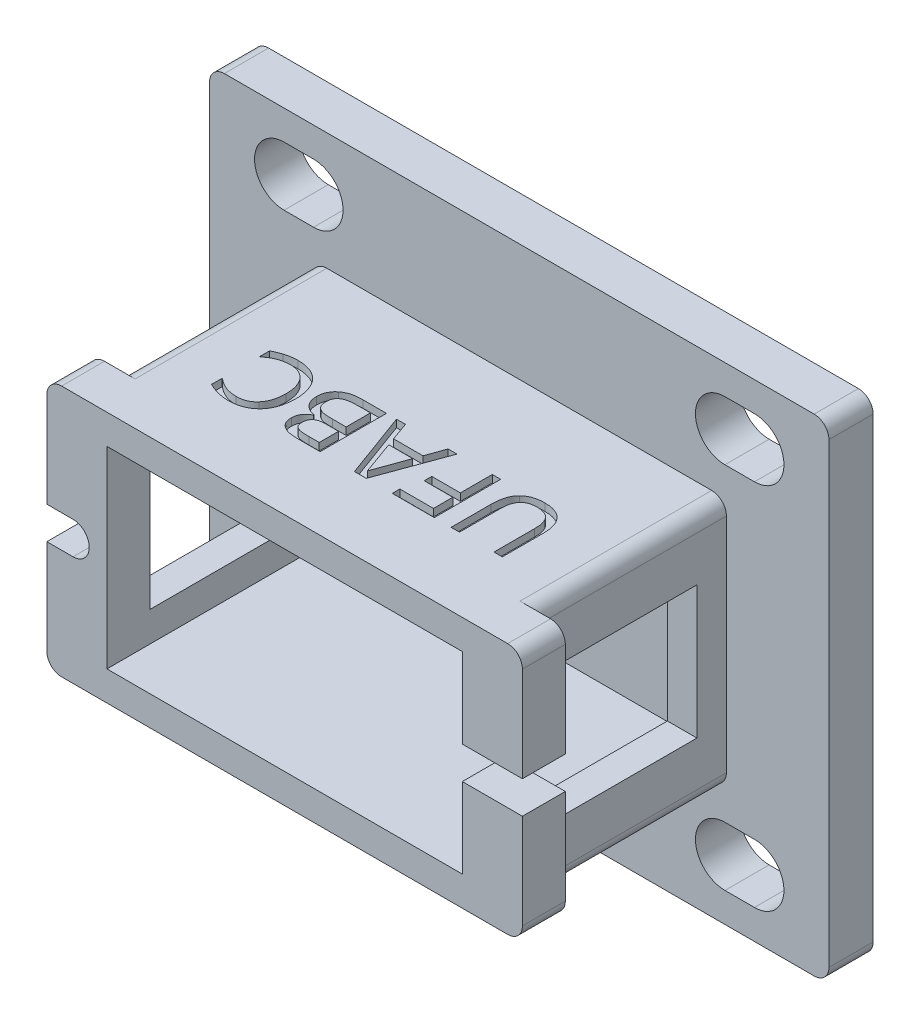
SolidWorks part; units mm, degrees
material "ABS"
ref_plane "Plano frontal" through (0, 0, 0) normal (0, 0, 1) x (1, 0, 0)
ref_plane "Plano superior" through (0, 0, 0) normal (0, 1, 0) x (1, 0, 0)
ref_plane "Plano direito" through (0, 0, 0) normal (1, 0, 0) x (0, 0, -1)
sketch "Esboço1" plane through (0, 0, 0) normal (0, 0, 1) x (1, 0, 0)
  line L0 (5.5315, 35.935) -> (5.5315, 2.935) construction
  line L19 (-14.4685, 35.935) -> (25.5315, 35.935)
  line L20 (-15.4685, 34.935) -> (-15.4685, 3.935)
  line L21 (-14.4685, 2.935) -> (25.5315, 2.935)
  line L22 (26.5315, 34.935) -> (26.5315, 3.935)
  arc A0 (26.5315, 34.935) -> (25.5315, 35.935) centre (25.5315, 34.935) ccw
  arc A1 (26.5315, 3.935) -> (25.5315, 2.935) centre (25.5315, 3.935) cw
  arc A2 (-14.4685, 2.935) -> (-15.4685, 3.935) centre (-14.4685, 3.935) cw
  arc A3 (-15.4685, 34.935) -> (-14.4685, 35.935) centre (-14.4685, 34.935) cw
  point P14 (-15.4685, 35.935)
  dimension "D3" = 1
  dimension "D1" = 33
  dimension "D2" = 42
extrude "Ressalto-extrusão1" add sketch "Esboço1" along normal blind 3
sketch "Esboço2" plane through (0, 0, 3) normal (0, 0, 1) x (1, 0, 0)
  line L0 (5.5315, 35.935) -> (5.5315, 2.935) construction
  line L1 (25.5315, 35.935) -> (-14.4685, 35.935) construction
  line L2 (-14.4685, 2.935) -> (25.5315, 2.935) construction
  line L3 (-15.4685, 19.435) -> (26.5315, 19.435) construction
  line L4 (-6.5185, 25.97) -> (17.5815, 25.97)
  line L5 (-6.5185, 25.97) -> (-6.5185, 12.9)
  line L6 (-6.5185, 12.9) -> (17.5815, 12.9)
  line L7 (17.5815, 25.97) -> (17.5815, 12.9)
  line L8 (-8.5185, 27.975) -> (19.5815, 27.975)
  line L9 (-8.5185, 27.975) -> (-8.5185, 10.895)
  line L10 (-8.5185, 10.895) -> (19.5815, 10.895)
  line L11 (19.5815, 27.975) -> (19.5815, 10.895)
  line L12 (-15.4685, 34.935) -> (-15.4685, 3.935) construction
  line L13 (26.5315, 3.935) -> (26.5315, 34.935) construction
  dimension "D1" = 14.05
  dimension "D2" = 14.05
  dimension "D3" = 12.05
  dimension "D4" = 12.05
  dimension "D5" = 8.54
  dimension "D6" = 8.54
  dimension "D7" = 6.535
  dimension "D8" = 6.535
extrude "Ressalto-extrusão2" add sketch "Esboço2" along normal blind 15.91
sketch "Esboço3" plane through (0, 0, 18.91) normal (0, 0, 1) x (1, 0, 0)
  line L0 (5.5315, 25.97) -> (5.5315, 10.895) construction
  line L1 (17.5815, 25.97) -> (-6.5185, 25.97) construction
  line L2 (-8.5185, 10.895) -> (19.5815, 10.895) construction
  line L3 (-15.4685, 19.435) -> (26.5315, 19.435) construction
  line L4 (-15.4685, 34.935) -> (-15.4685, 3.935) construction
  line L5 (26.5315, 3.935) -> (26.5315, 34.935) construction
  line L6 (19.5815, 27.975) -> (-8.5185, 27.975) construction
  line L7 (-8.5185, 27.975) -> (-9.5935, 27.975)
  line L8 (-8.5185, 27.975) -> (-8.5185, 10.895)
  line L9 (-8.5185, 10.895) -> (-9.5935, 10.895)
  line L10 (-10.5935, 26.975) -> (-10.5935, 11.895)
  line L11 (19.5815, 27.975) -> (20.6565, 27.975)
  line L12 (19.5815, 27.975) -> (19.5815, 10.895)
  line L13 (19.5815, 10.895) -> (20.6565, 10.895)
  line L14 (21.6565, 26.975) -> (21.6565, 11.895)
  line L16 (19.5815, 27.975) -> (-8.5185, 27.975) construction
  arc A0 (20.6565, 27.975) -> (21.6565, 26.975) centre (20.6565, 26.975) cw
  arc A1 (20.6565, 10.895) -> (21.6565, 11.895) centre (20.6565, 11.895) ccw
  arc A2 (-9.5935, 10.895) -> (-10.5935, 11.895) centre (-9.5935, 11.895) cw
  arc A3 (-9.5935, 27.975) -> (-10.5935, 26.975) centre (-9.5935, 26.975) ccw
  dimension "D3" = 1
  dimension "D1" = 16.125
  dimension "D2" = 16.125
extrude "Ressalto-extrusão3" add sketch "Esboço3" along direction (0, 0, 1) on the side against the normal offset from surface (2.91 mm away) 13
hole_wizard "Furo com folga de #00002" positions "Esboço8" profile "Esboço7" hole size "#0000" standard "Ansi Inch"
sketch "Esboço8" plane through (0, 0, 18.91) normal (0, 0, 1) x (1, 0, 0)
  line L0 (-10.5935, 19.435) -> (21.6565, 19.435) construction
  line L1 (-10.5935, 26.975) -> (-10.5935, 11.895) construction
  line L2 (21.6565, 11.895) -> (21.6565, 26.975) construction
  line L3 (-6.5185, 25.97) -> (-6.5185, 12.9) construction
  line L4 (17.5815, 12.9) -> (17.5815, 25.97) construction
  point P0 (-8.8185, 19.435)
  point P2 (19.8815, 19.435)
  dimension "D1" = 2.3
  dimension "D2" = 2.3
sketch "Esboço7" plane through (-8.8185, 19.435, 18.91) normal (1, 0, 0) x (0, -1, 0)
  line L0 (0, 0) -> (0, 4.6609)
  line L1 (0, 4.6609) -> (1.1, 4)
  line L2 (1.1, 4) -> (1.1, 0)
  line L5 (1.1, 0) -> (0, 0)
  line L10 (0, 4.6609) -> (-1.1, 4) construction
  line L11 (0, -6.35) -> (0, 107.95) construction
  dimension "Hole Dia." = 2.2
  dimension "Hole Depth" = 4
  dimension "Drill Angle" = 118
ref_plane "Plano1" through (0, 19.435, 0) normal (0, -1, 0) x (-1, 0, 0)
ref_plane "Plano2" through (5.5315, 0, 0) normal (-1, 0, 0) x (0, 0, 1)
sketch "Esboço19" plane through (0, 0, 3) normal (0, 0, 1) x (1, 0, 0)
  line L1 (-8.5185, 10.895) -> (-11.9435, 6.935) construction
  line L2 (-11.9435, 6.935) -> (-8.4185, 6.935) construction
  line L3 (-10.4185, 6.935) -> (-8.4185, 6.935) construction
  line L4 (-10.4185, 8.935) -> (-8.4185, 8.935)
  line L8 (-10.4185, 4.935) -> (-8.4185, 4.935)
  line L10 (-8.5185, 10.895) -> (-9.4185, 6.935) construction
  arc A0 (-10.4185, 8.935) -> (-10.4185, 4.935) centre (-10.4185, 6.935) ccw
  arc A1 (-8.4185, 4.935) -> (-8.4185, 8.935) centre (-8.4185, 6.935) ccw
  point P3 (-9.4185, 6.935)
  dimension "D1" = 4
  dimension "D2" = 6
extrude "Corte-extrusão5" cut sketch "Esboço19" against normal blind 10
mirror "Espelhar5" about plane through (0, 19.435, 0) normal (0, -1, 0) of "Corte-extrusão5"
mirror "Espelhar6" about plane through (5.5315, 0, 0) normal (-1, 0, 0) of "Corte-extrusão5"
mirror "Espelhar7" about plane through (0, 19.435, 0) normal (0, -1, 0) of "Espelhar6"
sketch "Esboço20" plane through (0, 0, 18.91) normal (0, 0, 1) x (1, 0, 0)
  line L0 (-10.5935, 19.435) -> (21.6565, 19.435) construction
  line L1 (-10.5935, 26.975) -> (-10.5935, 11.895) construction
  line L2 (21.6565, 11.895) -> (21.6565, 26.975) construction
  line L3 (-10.5935, 19.435) -> (-8.8185, 19.435) construction
  line L4 (-10.5935, 20.535) -> (-8.8185, 20.535)
  line L5 (-10.5935, 18.335) -> (-8.8185, 18.335)
  arc A0 (-10.5935, 20.535) -> (-10.5935, 18.335) centre (-10.5935, 19.435) ccw
  arc A1 (-8.8185, 18.335) -> (-8.8185, 20.535) centre (-8.8185, 19.435) ccw
  point P9 (-9.706, 19.435)
  dimension "D1" = 2.2
extrude "Corte-extrusão7" cut sketch "Esboço20" against normal blind 10
mirror "Espelhar8" about plane through (5.5315, 0, 0) normal (-1, 0, 0) of "Corte-extrusão7"
fillet "Filete3" radius 1 1 edges at (-8.5185, 27.975, 9.5)
fillet "Filete4" radius 1 1 edges at (-8.5185, 10.895, 9.5)
fillet "Filete5" radius 1 1 edges at (19.5815, 27.975, 9.5)
fillet "Filete6" radius 1 1 edges at (19.5815, 10.895, 9.5)
sketch "Esboço21" plane through (19.5815, 0, 0) normal (1, 0, 0) x (0, 0, -1)
  line L0 (-8.91, 19.435) -> (-20.3168, 19.435) construction
  line L1 (-8.91, 18.3767) -> (-8.91, 20.4933) construction
  line L3 (-16, 23.935) -> (-5, 23.935)
  line L4 (-16, 19.435) -> (-5, 19.435)
  line L5 (-16, 23.935) -> (-16, 14.935)
  line L6 (-16, 14.935) -> (-5, 14.935)
  line L7 (-5, 23.935) -> (-5, 14.935)
  dimension "D1" = 11
  dimension "D2" = 4.5
extrude "Corte-extrusão8" cut sketch "Esboço21" against normal blind 4
mirror "Espelhar9" about plane through (5.5315, 0, 0) normal (-1, 0, 0) of "Corte-extrusão8"
sketch "Esboço23" plane through (0, 27.975, 0) normal (0, 1, 0) x (1, 0, 0)
  line L0 (18.5815, -9.5) -> (-7.5185, -9.5) construction
  line L1 (18.5815, -16) -> (18.5815, -3) construction
  line L2 (-7.5185, -3) -> (-7.5185, -16) construction
  line L3 (18.5815, -4.2747) -> (-7.5185, -4.2747) construction
  text T0 "UFABC" font "Verdana" height 4.5
extrude "Corte-extrusão9" cut sketch "Esboço23" against normal blind 0.5
sketch "Esboço24" plane through (0, 10.895, 0) normal (0, -1, 0) x (1, 0, 0)
  line L0 (18.5815, 9.5) -> (-7.5185, 9.5) construction
  line L1 (18.5815, 3) -> (18.5815, 16) construction
  line L2 (-7.5185, 16) -> (-7.5185, 3) construction
  text T0 "CAD/CAM" font "Verdana" height 3.5
extrude "Corte-extrusão10" cut sketch "Esboço24" against normal blind 0.5
sketch "Esboço25" plane through (0, 0, 18.91) normal (0, 0, 1) x (1, 0, 0)
  line L1 (19.8815, 18.335) -> (17.5815, 18.335)
  line L2 (17.5815, 19.435) -> (21.5595, 19.435) construction
  line L3 (17.5815, 12.9) -> (17.5815, 25.97) construction
  line L4 (17.5815, 18.335) -> (17.5815, 20.535)
  line L5 (19.8815, 20.535) -> (17.5815, 20.535)
  line L6 (19.8815, 20.535) -> (19.8815, 18.335)
extrude "Corte-extrusão11" cut sketch "Esboço25" against normal blind 3
